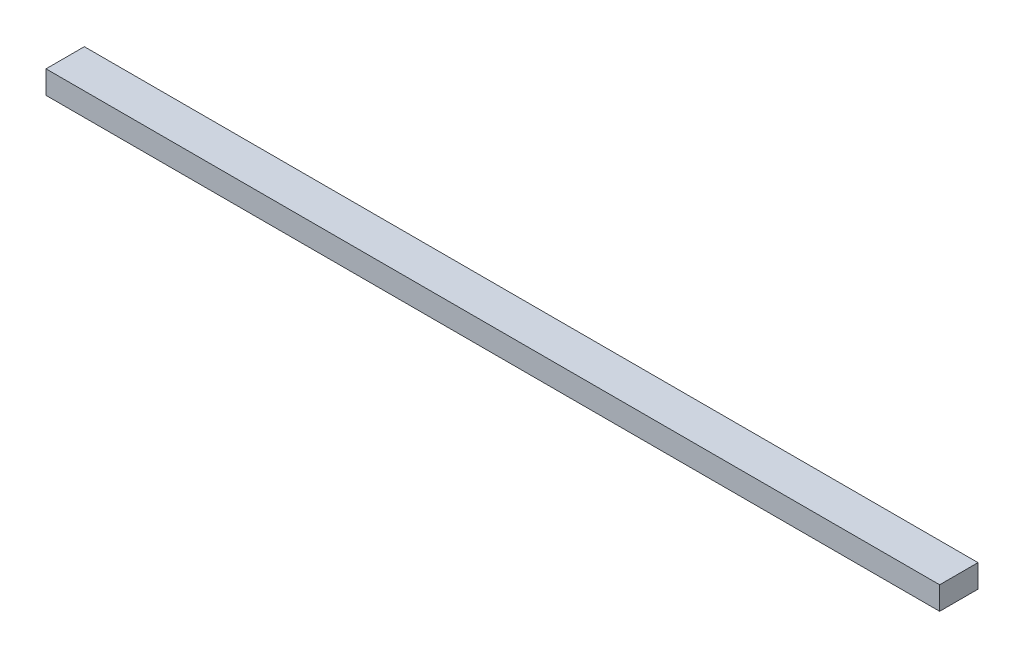
SolidWorks part; units mm, degrees
material "Pine"
ref_plane "Front Plane" through (0, 0, 0) normal (0, 0, 1) x (1, 0, 0)
ref_plane "Top Plane" through (0, 0, 0) normal (0, 1, 0) x (1, 0, 0)
ref_plane "Right Plane" through (0, 0, 0) normal (1, 0, 0) x (0, 0, -1)
sketch "Sketch1" plane through (0, 0, 0) normal (0, 1, 0) x (1, 0, 0)
  line L0 (0, 50) -> (2330, 50) construction
  line L1 (0, 0) -> (2330, 0)
  line L2 (0, 0) -> (0, 100)
  line L3 (0, 100) -> (2330, 100)
  line L4 (2330, 0) -> (2330, 100)
  dimension "D1" = 100
  dimension "D2" = 2330
extrude "Boss-Extrude1" add sketch "Sketch1" along normal blind 60
